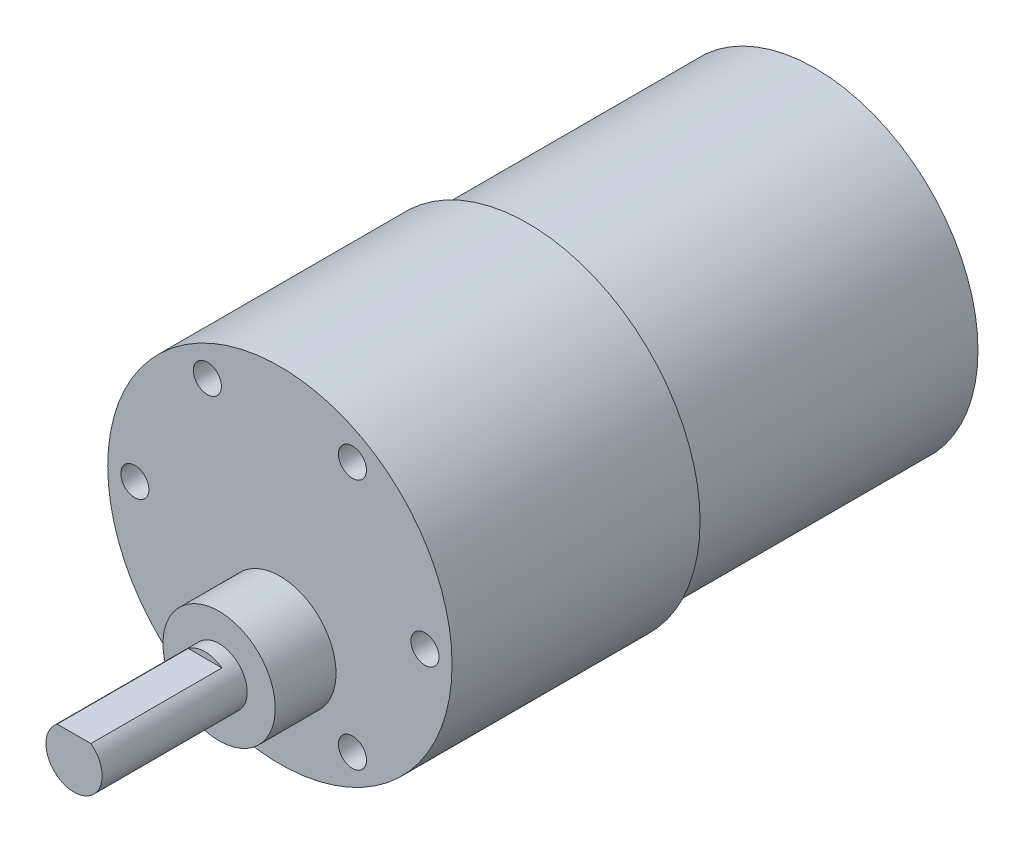
SolidWorks part; units mm, degrees
ref_plane "Front Plane" through (0, 0, 0) normal (0, 0, 1) x (1, 0, 0)
ref_plane "Top Plane" through (0, 0, 0) normal (0, 1, 0) x (1, 0, 0)
ref_plane "Right Plane" through (0, 0, 0) normal (1, 0, 0) x (0, 0, -1)
ref_plane "Plane1" through (0, 0, 26.5) normal (0, 0, 1) x (1, 0, 0)
ref_plane "Plane2" through (0, 0, -30.7) normal (0, 0, 1) x (1, 0, 0)
sketch "Sketch1" plane through (0, 0, 26.5) normal (0, 0, 1) x (1, 0, 0)
  circle A0 centre (0, 0) radius 18.4
  dimension "D1" = 36.8
extrude "Boss-Extrude1" add sketch "Sketch1" against normal up to surface (26.5 mm away) contours A0 up to plane "Front Plane"
sketch "Sketch2" plane through (0, 0, 0) normal (0, 0, 1) x (1, 0, 0)
  circle A0 centre (0, 0) radius 17.4
  dimension "D1" = 34.8
extrude "Boss-Extrude2" add sketch "Sketch2" against normal up to surface (30.7 mm away) up to plane "Plane2"
sketch "Sketch3" plane through (0, 0, 26.5) normal (0, 0, 1) x (1, 0, 0)
  line L0 (-18.4, 0) -> (18.4, 0) construction
  line L1 (0, 0) -> (0, -18.4) construction
  circle A0 centre (0, 0) radius 18.4 construction
  circle A1 centre (0, -7) radius 6
  dimension "D2" = 12
  dimension "D1" = 7
extrude "Boss-Extrude3" add sketch "Sketch3" along normal blind 6.5
sketch "Sketch4" plane through (0, 0, 33) normal (0, 0, 1) x (1, 0, 0)
  circle A0 centre (0, -7) radius 3
  dimension "D1" = 6
extrude "Boss-Extrude4" add sketch "Sketch4" along normal blind 15.5
sketch "Sketch5" plane through (0, 0, 48.5) normal (0, 0, 1) x (1, 0, 0)
  line L0 (-4.4114, -4.6) -> (4.4129, -4.6)
  line L1 (-4.4114, -4.6) -> (0, -0.4179)
  line L2 (0, -0.4179) -> (4.4129, -4.6)
  line L3 (0, -10) -> (0, -0.4179) construction
  circle A0 centre (0, -7) radius 3 construction
  dimension "D1" = 5.4
  dimension "D2" = 8.8243
  dimension "D3" = 316.529
extrude "Cut-Extrude1" cut sketch "Sketch5" against normal blind 14
sketch "Sketch6" plane through (0, 0, 26.5) normal (0, 0, 1) x (1, 0, 0)
  circle A0 centre (0, 0) radius 15.5 construction
  circle A1 centre (-15.5, 0) radius 1.5
  circle A2 centre (-7.75, 13.4234) radius 1.5
  circle A3 centre (7.75, 13.4234) radius 1.5
  circle A4 centre (15.5, 0) radius 1.5
  circle A5 centre (7.75, -13.4234) radius 1.5
  circle A6 centre (-7.75, -13.4234) radius 1.5
  point P17 (0, 0)
  dimension "D1" = 31
  dimension "D2" = 3
  dimension "D3" = 6
extrude "Cut-Extrude2" cut sketch "Sketch6" against normal blind 8
